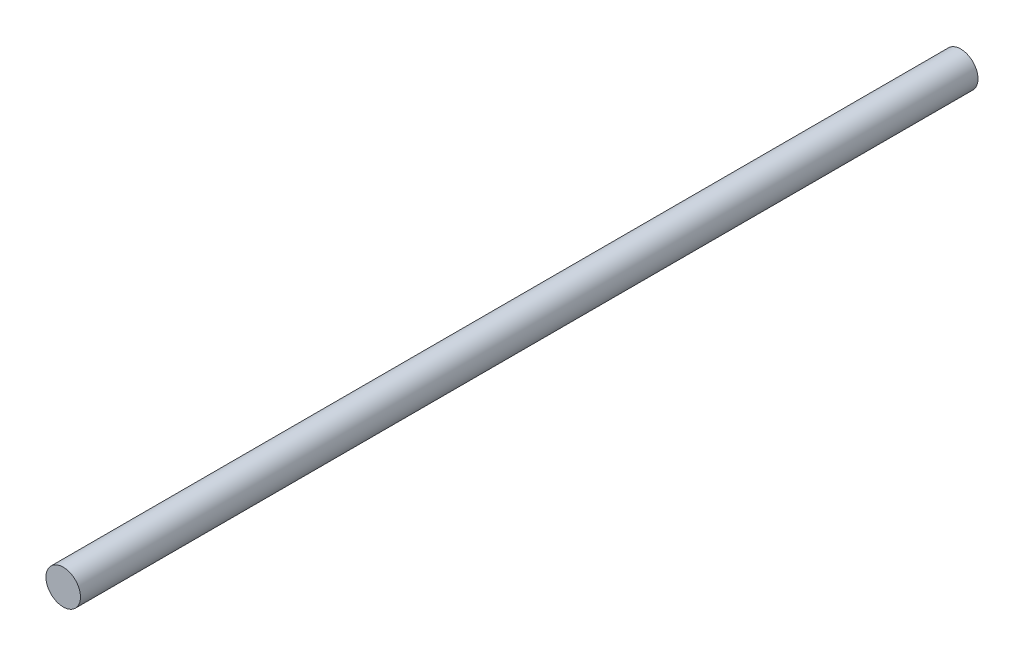
SolidWorks part; units mm, degrees
ref_plane "前视基准面" through (0, 0, 0) normal (0, 0, 1) x (1, 0, 0)
ref_plane "上视基准面" through (0, 0, 0) normal (0, 1, 0) x (1, 0, 0)
ref_plane "右视基准面" through (0, 0, 0) normal (1, 0, 0) x (0, 0, -1)
sketch "草图7" plane through (0, 0, 0) normal (0, 0, 1) x (1, 0, 0)
  circle A0 centre (0, 0) radius 2.5
  dimension "D1" = 5
curve "曲线3"
  spline degree 1 poles (0, 0, 0) (0, 0, 130) knots 0 0 1 1
sweep "扫描3" add profiles "草图7" path "曲线3"
